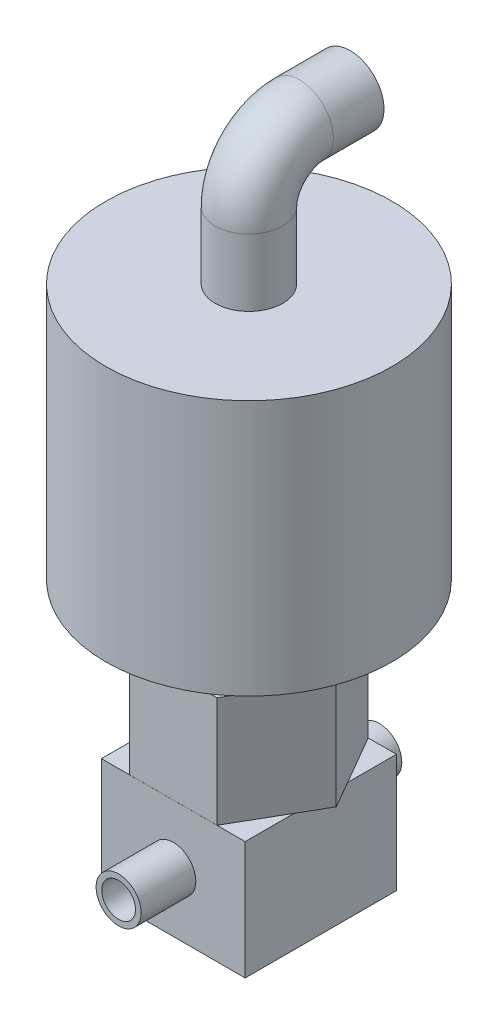
SolidWorks part; units mm, degrees
material "AISI 316 Annealed Stainless Steel Bar (SS)"
ref_plane "Front Plane" through (0, 0, 0) normal (0, 0, 1) x (1, 0, 0)
ref_plane "Top Plane" through (0, 0, 0) normal (0, 1, 0) x (1, 0, 0)
ref_plane "Right Plane" through (0, 0, 0) normal (1, 0, 0) x (0, 0, -1)
sketch "Sketch1" plane through (0, 0, 0) normal (1, 0, 0) x (0, 0, -1)
  line L0 (0, 0) -> (0, -25530.8142) construction
  line L1 (0, 0) -> (12.7, 0)
  line L2 (12.7, 0) -> (12.7, 22.2123)
  line L3 (12.7, 22.2123) -> (14.2176, 22.2123)
  line L4 (14.2176, 22.2123) -> (14.2176, 42.9768)
  line L5 (14.2176, 42.9768) -> (9.4234, 42.9768)
  line L6 (9.4234, 42.9768) -> (9.4234, 51.0667)
  line L7 (9.4234, 51.0667) -> (26.924, 51.0667)
  line L8 (26.924, 51.0667) -> (26.924, 99.1743)
  line L9 (26.924, 99.1743) -> (0, 99.1743)
  line L10 (0, 99.1743) -> (0, 0)
  dimension "D1" = 53.848
  dimension "D2" = 18.8468
  dimension "D3" = 28.4353
  dimension "D4" = 25.4
  dimension "D5" = 22.2123
  dimension "D6" = 99.1743
  dimension "D7" = 48.1076
  dimension "D8" = 20.7645
revolve "BASE" add sketch "Sketch1" angle 360 about L0
sketch "Sketch2" plane through (0, 0, 0) normal (0, -1, 0) x (1, 0, 0)
  line L1 (-13.5128, -14.224) -> (13.5128, -14.224)
  line L2 (-13.5128, -14.224) -> (-13.5128, 14.224)
  line L3 (-13.5128, 14.224) -> (13.5128, 14.224)
  line L4 (13.5128, -14.224) -> (13.5128, 14.224)
  line L5 (-13.5128, -14.224) -> (13.5128, 14.224) construction
  line L6 (-13.5128, 14.224) -> (13.5128, -14.224) construction
  point P0 (0, 0)
  dimension "D1" = 27.0256
  dimension "D2" = 28.448
extrude "MOUNT_BLOCK" add sketch "Sketch2" against normal up to surface (22.2123 mm away) up to face at (0, 22.2123, 14.2176)
sketch "Sketch3" plane through (0, 22.2123, 0) normal (0, -1, 0) x (1, 0, 0)
  line L1 (16.4171, 0) -> (8.2086, 14.2177)
  line L2 (8.2086, 14.2177) -> (-8.2086, 14.2177)
  line L3 (-8.2086, 14.2177) -> (-16.4171, 0)
  line L4 (-16.4171, 0) -> (-8.2086, -14.2177)
  line L5 (-8.2086, -14.2177) -> (8.2086, -14.2177)
  line L6 (8.2086, -14.2177) -> (16.4171, 0)
  circle A0 centre (0, 0) radius 14.2176 construction
  arc A1 (-13.5128, 4.4211) -> (-13.5128, -4.4211) centre (0, 0) ccw construction
  point P1 (0, 0)
extrude "MID_HEX" add sketch "Sketch3" against normal up to surface (20.7645 mm away) up to face at (0, 42.9768, 9.4234)
sketch "Sketch4" plane through (0, 0, 14.224) normal (0, 0, 1) x (1, 0, 0)
  line L0 (0, 22.2123) -> (0, 0) construction
  line L1 (13.5128, 22.2123) -> (-13.5128, 22.2123) construction
  line L2 (13.5128, 0) -> (-13.5128, 0) construction
  circle A0 centre (0, 11.1062) radius 4.2333
  circle A1 centre (0, 11.1062) radius 3.175
  dimension "D1" = 6.35
  dimension "D2" = 8.4667
extrude "SWGLK_M" add sketch "Sketch4" along normal blind 10.287
mirror "SWGLK_M_MRR" about plane through (0, 0, 0) normal (0, 0, 1) of "SWGLK_M"
sketch "Sketch5" plane through (0, 0, 0) normal (1, 0, 0) x (0, 0, -1)
  line L0 (0, 99.1743) -> (0, 111.7676)
  line L1 (26.924, 99.1743) -> (-26.924, 99.1743) construction
  line L2 (9.525, 121.2926) -> (19.05, 121.2926)
  arc A0 (0, 111.7676) -> (9.525, 121.2926) centre (9.525, 111.7676) cw
  point P8 (0, 121.2926)
  dimension "D3" = 9.525
  dimension "D1" = 22.1183
  dimension "D2" = 19.05
sketch "Sketch6" plane through (0, 99.1743, 0) normal (0, 1, 0) x (1, 0, 0)
  circle A0 centre (0, 0) radius 6.35
  circle A1 centre (0, 0) radius 3.175
  dimension "D1" = 12.7
  dimension "D2" = 6.35
sweep "PRESS_QD" add profiles "Sketch6" path "Sketch5"
sketch "Sketch7" plane through (0, 0, 0) normal (0, -1, 0) x (1, 0, 0)
  line L0 (-9.0889, -11.6328) -> (35085.7658, -30315.6294) construction
  line L1 (-8.296, -9.6076) -> (8.296, -9.6076) construction
  line L2 (-8.296, -9.6076) -> (-8.296, 9.6076) construction
  line L3 (-8.296, 9.6076) -> (8.296, 9.6076) construction
  line L4 (8.296, -9.6076) -> (8.296, 9.6076) construction
  line L5 (-8.296, -9.6076) -> (8.296, 9.6076) construction
  line L6 (-8.296, 9.6076) -> (8.296, -9.6076) construction
  line L7 (10.239, 10.6396) -> (37854.161, -32667.1444) construction
  line L8 (13.5128, 14.224) -> (-13.5128, 14.224) construction
  circle A0 centre (-8.296, -9.6076) radius 2.0511
  circle A1 centre (8.296, 9.6076) radius 2.0511
  point P0 (0, 0)
  point P12 (8.296, 11.6586)
  dimension "D1" = 4.1021
  dimension "D2" = 29.4894
  dimension "D3" = 2.5654
extrude "MOUNT_HOLES" cut sketch "Sketch7" against normal blind 12.7
